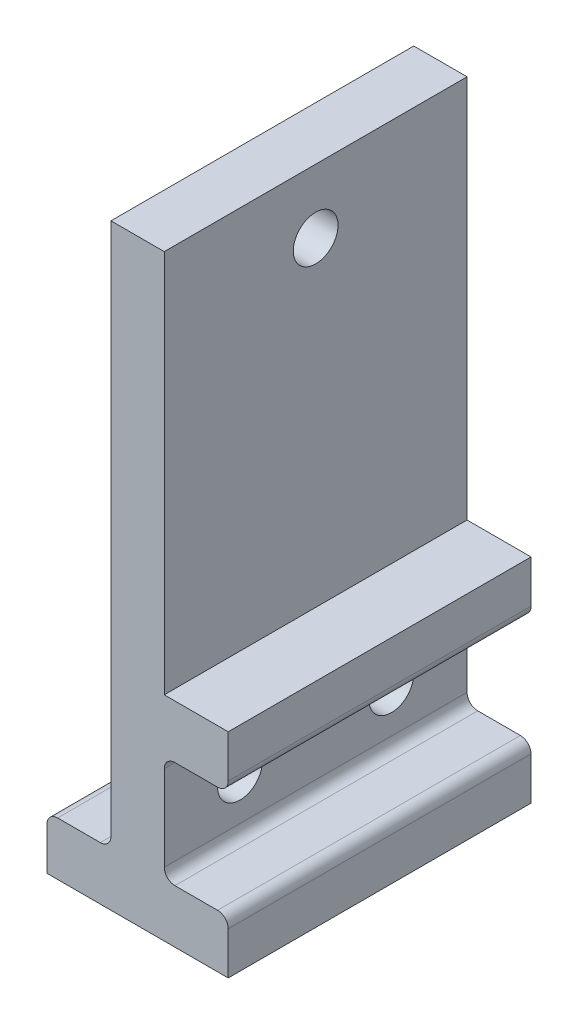
SolidWorks part; units mm, degrees
ref_plane "Front Plane" through (0, 0, 0) normal (0, 0, 1) x (1, 0, 0)
ref_plane "Top Plane" through (0, 0, 0) normal (0, 1, 0) x (1, 0, 0)
ref_plane "Right Plane" through (0, 0, 0) normal (1, 0, 0) x (0, 0, -1)
sketch "Sketch1" plane through (0, 0, 0) normal (0, 0, 1) x (1, 0, 0)
  line L0 (0, 0) -> (0, 10)
  line L1 (0, 10) -> (12, 10)
  line L2 (12, 10) -> (12, 112)
  line L3 (12, 112) -> (22, 112)
  line L4 (22, 112) -> (22, 40)
  line L5 (22, 40) -> (34, 40)
  line L6 (34, 40) -> (34, 30)
  line L7 (34, 30) -> (22, 30)
  line L11 (22, 30) -> (22, 10)
  line L12 (22, 10) -> (34, 10)
  line L13 (34, 10) -> (34, 0)
  line L15 (0, 0) -> (34, 0)
  dimension "D1" = 10
  dimension "D2" = 10
  dimension "D3" = 10
  dimension "D4" = 12
  dimension "D5" = 102
  dimension "D6" = 20
  dimension "D7" = 72
  dimension "D8" = 12
extrude "Boss-Extrude1" add sketch "Sketch1" along normal blind 56.8
sketch "Sketch2" plane through (12, 0, 0) normal (-1, 0, 0) x (0, 0, 1)
  line L0 (28.4, 112) -> (28.4, 0) construction
  line L1 (56.8, 112) -> (0, 112) construction
  line L2 (56.8, 0) -> (0, 0) construction
  line L3 (56.8, 112) -> (56.8, 10) construction
  line L4 (0, 112) -> (0, 10) construction
  line L5 (56.8, 112) -> (56.8, 10) construction
  line L6 (0, 112) -> (0, 10) construction
  line L8 (56.8, 30) -> (0, 30) construction
  line L10 (56.8, 30) -> (0, 30) construction
  line L11 (14.2, 112) -> (14.2, 10) construction
  line L12 (0, 10) -> (28.4, 10) construction
  line L13 (0, 30) -> (0, 10) construction
  line L14 (0, 20) -> (28.4, 20) construction
  circle A0 centre (14.2, 20) radius 4.2
  circle A1 centre (42.6, 20) radius 4.2
  dimension "D1" = 8.4
extrude "Cut-Extrude1" cut sketch "Sketch2" against normal up to next
sketch "Sketch4" plane through (12, 0, 0) normal (-1, 0, 0) x (0, 0, 1)
  line L0 (28.4, 112) -> (28.4, 0) construction
  line L1 (56.8, 112) -> (0, 112) construction
  line L2 (56.8, 0) -> (0, 0) construction
  circle A0 centre (28.4, 100) radius 4.2
  point P8 (0, 0)
  dimension "D1" = 8.4
  dimension "D2" = 12
extrude "Cut-Extrude3" cut sketch "Sketch4" against normal up to next
fillet "Fillet1" radius 2 6 edges at (12, 10, 28.4) (0, 10, 28.4) (34, 10, 28.4) (22, 10, 28.4) (22, 30, 28.4) (34, 30, 28.4)
